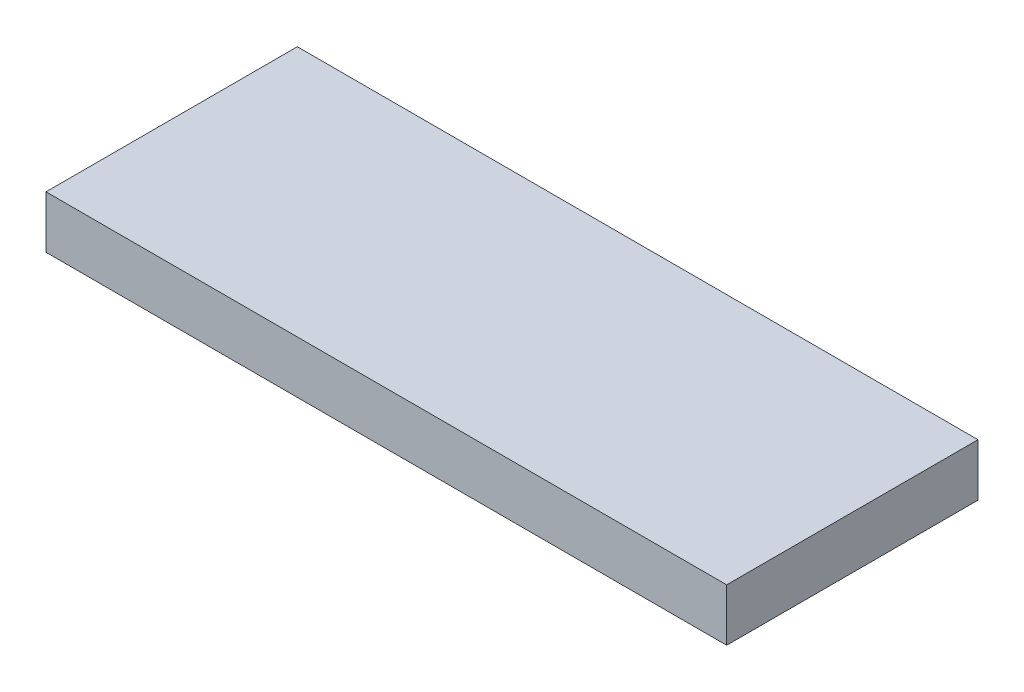
SolidWorks part; units mm, degrees
ref_plane "Front Plane" through (0, 0, 0) normal (0, 0, 1) x (1, 0, 0)
ref_plane "Top Plane" through (0, 0, 0) normal (0, 1, 0) x (1, 0, 0)
ref_plane "Right Plane" through (0, 0, 0) normal (1, 0, 0) x (0, 0, -1)
sketch "Sketch1" plane through (0, 0, 0) normal (0, 1, 0) x (1, 0, 0)
  line L1 (6.5, -2.4) -> (-6.5, -2.4)
  line L2 (6.5, -2.4) -> (6.5, 2.4)
  line L3 (6.5, 2.4) -> (-6.5, 2.4)
  line L4 (-6.5, -2.4) -> (-6.5, 2.4)
  line L5 (6.5, -2.4) -> (-6.5, 2.4) construction
  line L6 (6.5, 2.4) -> (-6.5, -2.4) construction
  point P0 (0, 0)
  dimension "D1" = 4.8
  dimension "D2" = 13
extrude "Boss-Extrude1" add sketch "Sketch1" along normal blind 1
